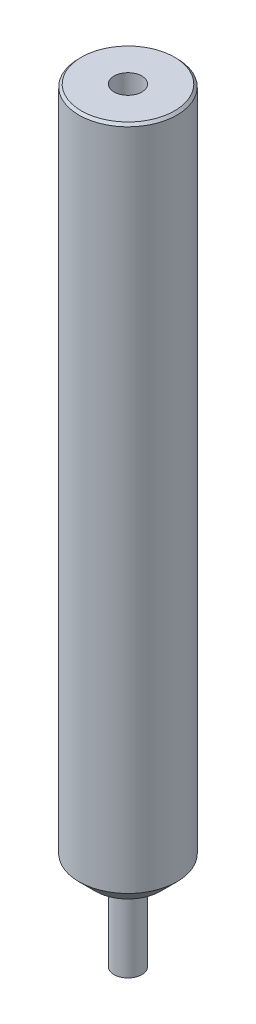
SolidWorks part; units mm, degrees
ref_plane "Plano frontal" through (0, 0, 0) normal (0, 0, 1) x (1, 0, 0)
ref_plane "Plano superior" through (0, 0, 0) normal (0, 1, 0) x (1, 0, 0)
ref_plane "Plano direito" through (0, 0, 0) normal (1, 0, 0) x (0, 0, -1)
ref_plane "Plano1" through (0, 0, 0) normal (0, 0, -1) x (-1, 0, 0)
sketch "Esboço1" plane through (0, 0, 0) normal (0, 0, -1) x (-1, 0, 0)
  line L0 (-1.7, 0) -> (0, 0)
  line L1 (0, 0) -> (0, 83.6)
  line L2 (0, 83.6) -> (-1.7, 83.6)
  line L3 (-1.7, 83.6) -> (-1.7, 93.6)
  line L4 (-1.7, 93.6) -> (-5.7, 93.6)
  line L5 (-5.7, 93.6) -> (-6, 93.3)
  line L6 (-6, 93.3) -> (-6, 12)
  line L7 (-6, 12) -> (-4, 10)
  line L8 (-4, 10) -> (-1.7, 10)
  line L9 (-1.7, 10) -> (-1.7, 0)
  line L10 (0, 0) -> (0, 93.6) construction
revolve "Revolução1" add sketch "Esboço1" angle 360 about L10
